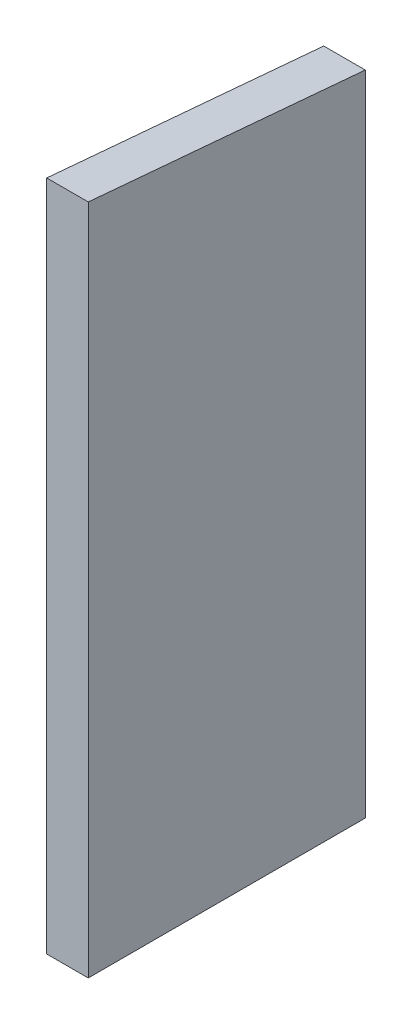
SolidWorks part; units mm, degrees
material "Cedro"
ref_plane "Alzado" through (0, 0, 0) normal (0, 0, 1) x (1, 0, 0)
ref_plane "Planta" through (0, 0, 0) normal (0, 1, 0) x (1, 0, 0)
ref_plane "Vista lateral" through (0, 0, 0) normal (1, 0, 0) x (0, 0, -1)
sketch "Croquis1" plane through (0, 0, 0) normal (0, 1, 0) x (1, 0, 0)
  line L1 (-7.5, -50) -> (7.5, -50)
  line L2 (-7.5, -50) -> (-7.5, 50)
  line L3 (-7.5, 50) -> (7.5, 50)
  line L4 (7.5, -50) -> (7.5, 50)
  line L5 (-7.5, -50) -> (7.5, 50) construction
  line L6 (-7.5, 50) -> (7.5, -50) construction
  point P0 (0, 0)
  dimension "D1" = 15
  dimension "D2" = 100
extrude "Saliente-Extruir1" add sketch "Croquis1" along normal blind 243.23
sketch "Croquis2" plane through (7.5, 0, 0) normal (1, 0, 0) x (0, 0, -1)
  line L0 (-50, 242.602) -> (50, 233.8532)
  line L1 (-50, 243.23) -> (-50, 0) construction
  line L2 (-192.0168, 255.0269) -> (-50, 242.602) construction
  line L3 (50, 243.23) -> (50, 0) construction
  line L4 (50, 233.8532) -> (50, 243.23)
  line L5 (50, 243.23) -> (-50, 243.23)
  line L6 (-50, 243.23) -> (-50, 242.602)
extrude "Cortar-Extruir1" cut sketch "Croquis2" against normal through all
